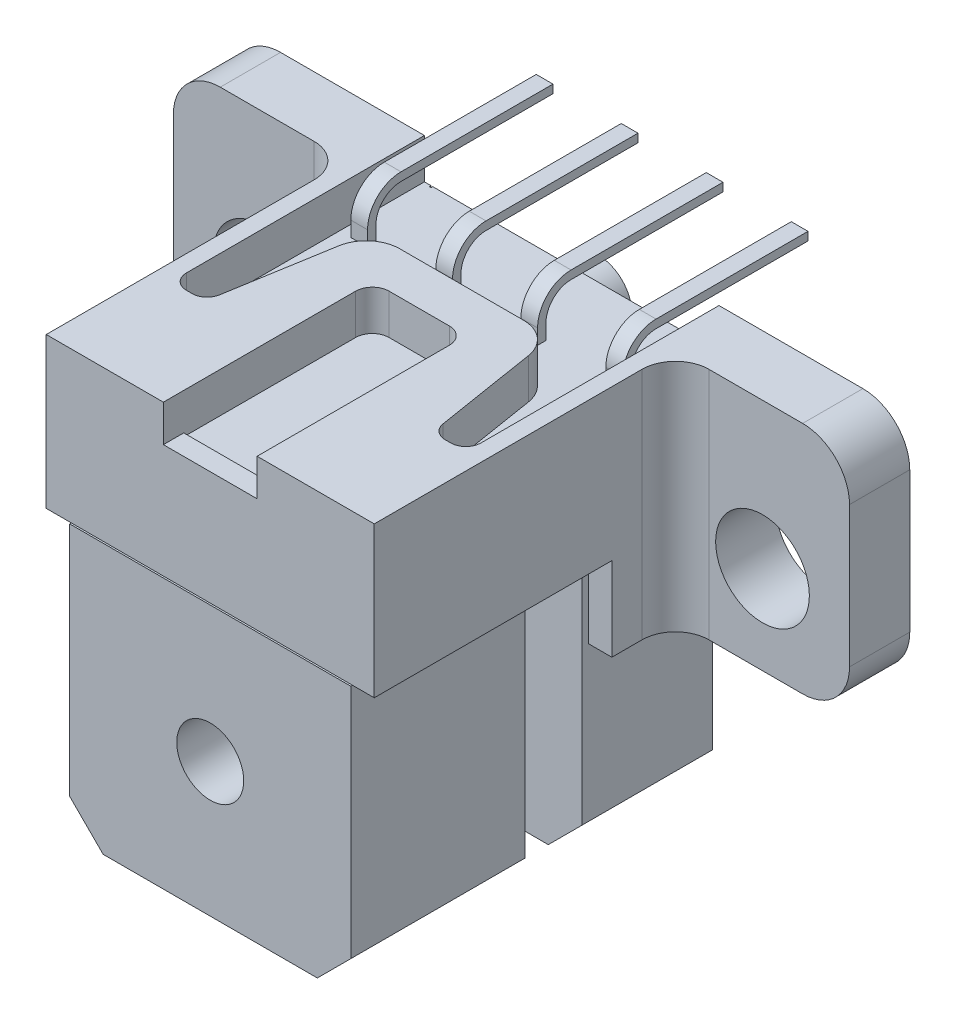
SolidWorks part; units mm, degrees
ref_plane "Спереди" through (0, 0, 0) normal (0, 0, 1) x (1, 0, 0)
ref_plane "Сверху" through (0, 0, 0) normal (0, 1, 0) x (1, 0, 0)
ref_plane "Справа" through (0, 0, 0) normal (1, 0, 0) x (0, 0, -1)
sketch "Эскиз1" plane through (0, 0, 0) normal (0, 0, 1) x (1, 0, 0)
  line L0 (7.4, 0) -> (8.4, 1)
  line L1 (1, 0) -> (7.4, 0)
  line L2 (0, 1) -> (0, 12.6)
  line L3 (0, 12.6) -> (8.4, 12.6)
  line L4 (8.4, 1) -> (8.4, 12.6)
  line L5 (0, 1) -> (1, 0)
  point P0 (0, 0)
  point P3 (8.4, 0)
  dimension "D1" = 12.6
  dimension "D2" = 8.4
extrude "Бобышка-Вытянуть1" add sketch "Эскиз1" along normal blind 10.8
sketch "Эскиз2" plane through (0, 0, 0) normal (0, 0, -1) x (-1, 0, 0)
  line L0 (-8.4, 12.6) -> (0, 12.6) construction
  circle A0 centre (-4.2, 10.3) radius 1
  circle A1 centre (-4.2, 3.9) radius 1
  dimension "D2" = 6.4
  dimension "D3" = 2
  dimension "D1" = 8.7
extrude "Бобышка-Вытянуть2" add sketch "Эскиз2" along normal blind 0.8
sketch "Эскиз3" plane through (8.4, 0, 0) normal (1, 0, 0) x (0, 0, -1)
  line L0 (-10.8, 0) -> (0, 0) construction
  line L1 (-3.9, 0) -> (-5.6, 0)
  line L2 (-3.9, 0) -> (-3.9, 8.1)
  line L3 (-3.9, 8.1) -> (-5.6, 8.1)
  line L4 (-5.6, 0) -> (-5.6, 8.1)
  line L5 (0, 12.6) -> (0, 1) construction
  line L6 (0.8, 2.9) -> (0.8, 4.9) construction
  line L7 (0.8, 3.9) -> (-1.4983, 3.9) construction
  dimension "D1" = 3.9
  dimension "D2" = 1.7
  dimension "D3" = 4.2
extrude "Вырез-Вытянуть1" cut sketch "Эскиз3" against normal blind 17.8
sketch "Эскиз4" plane through (0, 12.6, 0) normal (0, 1, 0) x (1, 0, 0)
  line L0 (9.1, -10.8) -> (-0.7, -10.8)
  line L1 (14.3, 0) -> (-5.9, 0)
  line L3 (8.4, 0) -> (0, 0) construction
  line L4 (14.3, 0) -> (14.3, -1.8)
  line L5 (14.3, -1.8) -> (10.1, -1.8)
  line L6 (9.1, -2.8) -> (9.1, -10.8)
  line L7 (-0.7, -10.8) -> (-0.7, -2.8)
  line L8 (-1.7, -1.8) -> (-5.9, -1.8)
  line L9 (-5.9, -1.8) -> (-5.9, 0)
  arc A0 (-0.7, -2.8) -> (-1.7, -1.8) centre (-1.7, -2.8) ccw
  arc A1 (10.1, -1.8) -> (9.1, -2.8) centre (10.1, -2.8) ccw
  point P5 (4.2, -10.8)
  point P9 (4.2, 0)
  dimension "D5" = 1
  dimension "D1" = 9.8
  dimension "D2" = 20.2
  dimension "D3" = 1.8
  dimension "D4" = 1.8
extrude "Бобышка-Вытянуть3" add sketch "Эскиз4" against normal up to vertex
sketch "Эскиз5" plane through (0, 0, 10.8) normal (0, 0, 1) x (1, 0, 0)
  line L0 (0, 8.1) -> (0, 1) construction
  line L1 (8.4, 8.1) -> (0, 8.1)
  line L2 (8.4, 8.1) -> (8.4, 8.05)
  line L3 (8.4, 8.05) -> (0, 8.05)
  line L4 (0, 8.1) -> (0, 8.05)
extrude "Вырез-Вытянуть2" cut sketch "Эскиз5" against normal blind 1
sketch "Эскиз6" plane through (0, 0, 10.8) normal (0, 0, 1) x (1, 0, 0)
  line L0 (1, 0) -> (7.4, 0) construction
  circle A0 centre (4.2, 4) radius 1
  dimension "D1" = 4
  dimension "D2" = 2
extrude "Вырез-Вытянуть3" cut sketch "Эскиз6" against normal blind 8
sketch "Эскиз7" plane through (0, 12.6, 0) normal (0, 1, 0) x (1, 0, 0)
  line L0 (8.6, 0) -> (8.6, -7.1124)
  line L1 (14.3, 0) -> (-5.9, 0) construction
  line L2 (8.15, -7.5624) -> (7.9834, -7.5624)
  line L3 (7.5391, -7.1839) -> (7.0497, -4.1412)
  line L4 (6.0624, -3.3) -> (2.3617, -3.3)
  line L5 (1.3755, -4.1344) -> (0.863, -7.1869)
  line L6 (0.4192, -7.5624) -> (0.25, -7.5624)
  line L7 (-0.2, -7.1124) -> (-0.2, 0)
  line L8 (9.1, -10.8) -> (9.1, -2.8) construction
  line L9 (-0.7, -2.8) -> (-0.7, -10.8) construction
  line L10 (8.6, 0) -> (-0.2, 0)
  line L11 (4.2, -10.8) -> (5.6, -10.8)
  line L12 (9.1, -10.8) -> (-0.7, -10.8) construction
  line L13 (5.6, -10.8) -> (5.6, -5.0564)
  line L14 (5.1, -4.5564) -> (3.3, -4.5564)
  line L15 (2.8, -5.0564) -> (2.8, -10.8)
  line L16 (2.8, -10.8) -> (4.2, -10.8)
  arc A0 (2.3617, -3.3) -> (1.3755, -4.1344) centre (2.3617, -4.3) ccw
  arc A1 (7.0497, -4.1412) -> (6.0624, -3.3) centre (6.0624, -4.3) ccw
  arc A2 (0.25, -7.5624) -> (-0.2, -7.1124) centre (0.25, -7.1124) cw
  arc A3 (0.863, -7.1869) -> (0.4192, -7.5624) centre (0.4192, -7.1124) cw
  arc A4 (7.9834, -7.5624) -> (7.5391, -7.1839) centre (7.9834, -7.1124) cw
  arc A5 (8.6, -7.1124) -> (8.15, -7.5624) centre (8.15, -7.1124) cw
  arc A6 (3.3, -4.5564) -> (2.8, -5.0564) centre (3.3, -5.0564) ccw
  arc A7 (5.6, -5.0564) -> (5.1, -4.5564) centre (5.1, -5.0564) ccw
  point P23 (-0.2, -7.5624)
  point P26 (0.8, -7.5624)
  point P29 (7.6, -7.5624)
  point P32 (8.6, -7.5624)
  dimension "D6" = 1
  dimension "D7" = 0.45
  dimension "D8" = 0.5
  dimension "D1" = 0.5
  dimension "D2" = 0.5
  dimension "D3" = 1
  dimension "D4" = 1
  dimension "D5" = 3.3
extrude "Вырез-Вытянуть4" cut sketch "Эскиз7" against normal blind 1.2
sketch "Эскиз8" plane through (0, 11.4, 0) normal (0, 1, 0) x (1, 0, 0)
  line L0 (2.8, -5.0564) -> (2.8, -10.8) construction
  line L1 (5.6, -10.8) -> (2.8, -10.8)
  line L2 (5.6, -10.8) -> (5.6, -10.1916)
  line L3 (5.6, -10.1916) -> (2.8, -10.1916)
  line L4 (2.8, -10.8) -> (2.8, -10.1916)
extrude "Бобышка-Вытянуть4" add sketch "Эскиз8" along normal blind 0.1
sketch "Эскиз9" plane through (0, 8.1, 0) normal (0, -1, 0) x (1, 0, 0)
  line L0 (0, 0) -> (0, 3.7)
  line L1 (0, 0) -> (0, 3.9) construction
  line L2 (0, 3.7) -> (-0.7, 3.7)
  line L3 (-0.7, 2.8) -> (-0.7, 10.8) construction
  line L4 (-0.7, 3.7) -> (-0.7, 2.8)
  line L5 (-1.7, 1.8) -> (-5.9, 1.8)
  line L6 (-5.9, 1.8) -> (-5.9, 0)
  line L7 (-5.9, 0) -> (0, 0)
  line L8 (14.3, 0) -> (8.4, 0)
  line L9 (8.4, 0) -> (8.4, 3.7)
  line L10 (8.4, 3.9) -> (8.4, 0) construction
  line L11 (8.4, 3.7) -> (9.1, 3.7)
  line L12 (9.1, 10.8) -> (9.1, 2.8) construction
  line L13 (9.1, 3.7) -> (9.1, 2.8)
  line L14 (1, 3.9) -> (0, 3.9) construction
  line L15 (10.1, 1.8) -> (14.3, 1.8)
  line L16 (14.3, 1.8) -> (14.3, 0)
  line L17 (0, 3.9) -> (8.4, 3.9) construction
  arc A0 (9.1, 2.8) -> (10.1, 1.8) centre (10.1, 2.8) ccw
  arc A1 (-0.7, 2.8) -> (-1.7, 1.8) centre (-1.7, 2.8) cw
  dimension "D1" = 0.2
  dimension "D2" = 0.2
extrude "Бобышка-Вытянуть5" add sketch "Эскиз9" along normal blind 2.5
sketch "Эскиз10" plane through (0, 8.1, 0) normal (0, -1, 0) x (1, 0, 0)
  line L1 (0, 3.9) -> (8.4, 3.9)
  line L2 (0, 3.9) -> (0, 5.6)
  line L3 (0, 5.6) -> (8.4, 5.6)
  line L4 (8.4, 3.9) -> (8.4, 5.6)
extrude "Вырез-Вытянуть5" cut sketch "Эскиз10" against normal blind 0.05
fillet "Скругление1" radius 1.4 4 edges at (-5.9, 5.6, 0.9) (-5.9, 12.6, 0.9) (14.3, 12.6, 0.9) (14.3, 5.6, 0.9)
sketch "Эскиз11" plane through (0, 0, 0) normal (0, 0, -1) x (-1, 0, 0)
  line L0 (-8.6, 11.4) -> (0.2, 11.4) construction
  line L1 (-8.4, 5.5617) -> (-8.35, 5.5617)
  line L2 (-8.4, 5.5617) -> (-8.4, 11.4)
  line L3 (-8.4, 11.4) -> (-8.35, 11.4)
  line L4 (-8.35, 5.5617) -> (-8.35, 11.4)
  line L6 (0, 5.5712) -> (-0.05, 5.5712)
  line L7 (0, 5.5712) -> (0, 11.4)
  line L8 (0, 11.4) -> (-0.05, 11.4)
  line L9 (-0.05, 5.5712) -> (-0.05, 11.4)
  point P12 (0, 0)
  point P13 (0, 0)
extrude "Вырез-Вытянуть8" cut sketch "Эскиз11" against normal blind 0.05 contours L9 L8 L7 L6 | L4 L3 L2 L1
sketch "Эскиз12" plane through (0, 0, 0) normal (0, 0, -1) x (-1, 0, 0)
  circle A0 centre (-11.7, 8.24) radius 1.4
  circle A1 centre (3.3, 8.24) radius 1.4
  circle A2 centre (-4.2, 10.3) radius 1 construction
  circle A3 centre (-4.2, 3.9) radius 1 construction
  circle A7 centre (-4.2, 3.9) radius 1 construction
  dimension "D1" = 7.5
  dimension "D3" = 2.8
  dimension "D5" = 4.34
  dimension "D2" = 7.5
  dimension "D4" = 2.8
  dimension "D6" = 4.34
extrude "Вырез-Вытянуть9" cut sketch "Эскиз12" against normal blind 4
sketch "Эскиз13" plane through (0, 11.4, 0) normal (0, 1, 0) x (1, 0, 0)
  line L5 (5.72, -2.54) -> (5.22, -2.54)
  line L6 (5.72, -2.54) -> (5.72, 3)
  line L7 (5.72, 3) -> (5.22, 3)
  line L8 (5.22, -2.54) -> (5.22, 3)
  line L9 (8.26, -2.54) -> (7.76, -2.54)
  line L10 (8.26, -2.54) -> (8.26, 3)
  line L11 (8.26, 3) -> (7.76, 3)
  line L12 (7.76, -2.54) -> (7.76, 3)
  line L13 (3.18, -2.54) -> (2.68, -2.54)
  line L14 (3.18, -2.54) -> (3.18, 3)
  line L15 (3.18, 3) -> (2.68, 3)
  line L16 (2.68, -2.54) -> (2.68, 3)
  line L17 (5.72, -2.54) -> (5.22, -2.54)
  line L18 (5.72, -2.54) -> (5.72, 3)
  line L19 (5.72, 3) -> (5.22, 3)
  line L20 (5.22, -2.54) -> (5.22, 3)
  line L21 (0.64, -2.54) -> (0.14, -2.54)
  line L22 (0.64, -2.54) -> (0.64, 3)
  line L23 (0.64, 3) -> (0.14, 3)
  line L24 (0.14, -2.54) -> (0.14, 3)
extrude "Бобышка-Вытянуть6" add sketch "Эскиз13" along normal blind 1.45 contours L5 L8 L7 L6 | L13 L16 L15 L14 | L21 L24 L23 L22 | L9 L12 L11 L10
fillet "Скругление2" radius 1 4 edges at (0.39, 12.85, 2.54) (2.93, 12.85, 2.54) (5.47, 12.85, 2.54) (8.01, 12.85, 2.54)
sketch "Эскиз14" plane through (0.14, 0, 0) normal (-1, 0, 0) x (0, 0, 1)
  line L0 (-3, 12.6) -> (1.54, 12.6)
  line L1 (-3, 12.85) -> (-3, 11.4) construction
  line L2 (2.29, 11.85) -> (2.29, 11.4)
  line L3 (0, 11.4) -> (7.1124, 11.4) construction
  line L4 (2.29, 11.4) -> (-3, 11.4)
  line L5 (-3, 11.4) -> (-3, 12.6)
  line L6 (1.54, 12.85) -> (-3, 12.85) construction
  line L7 (2.54, 11.85) -> (2.54, 11.4) construction
  arc A0 (1.54, 12.6) -> (2.29, 11.85) centre (1.54, 11.85) cw
  dimension "D3" = 0.75
  dimension "D1" = 0.25
  dimension "D2" = 0.25
extrude "Вырез-Вытянуть10" cut sketch "Эскиз14" against normal up to vertex
